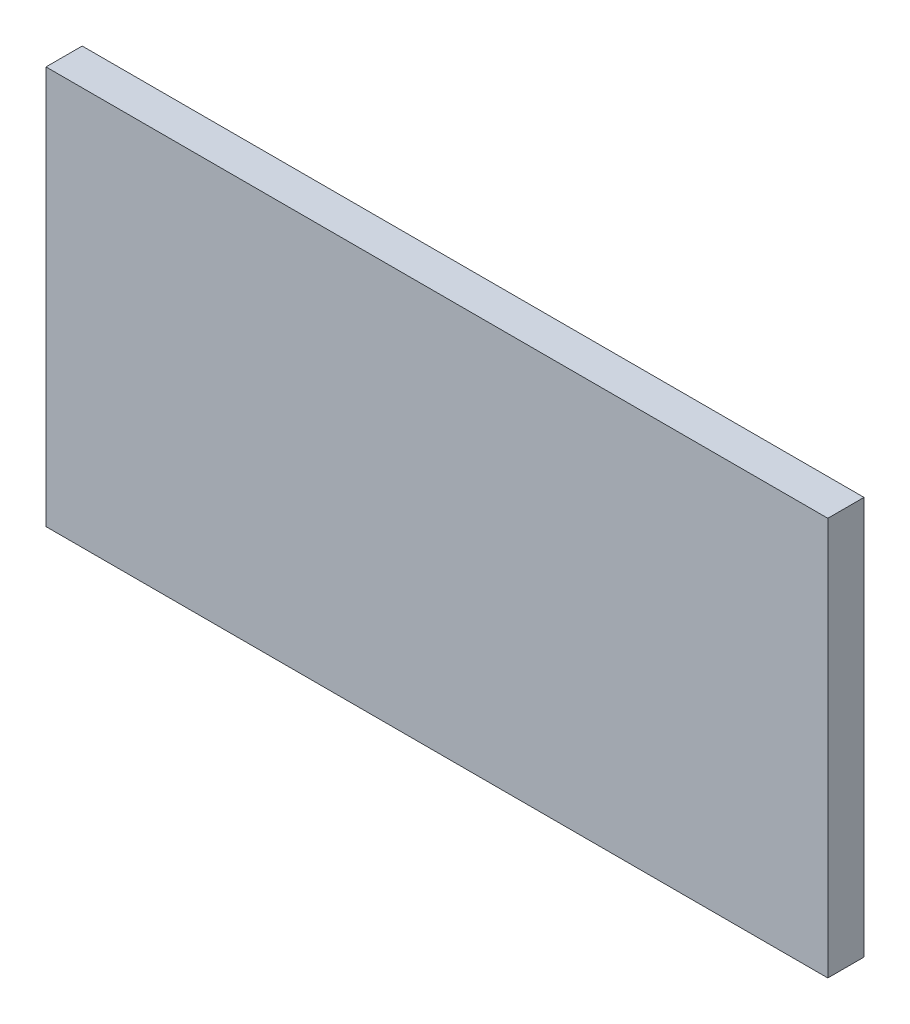
SolidWorks part; units mm, degrees
ref_plane "Front Plane" through (0, 0, 0) normal (0, 0, 1) x (1, 0, 0)
ref_plane "Top Plane" through (0, 0, 0) normal (0, 1, 0) x (1, 0, 0)
ref_plane "Right Plane" through (0, 0, 0) normal (1, 0, 0) x (0, 0, -1)
sketch "Sketch1" plane through (0, 0, 0) normal (0, 0, 1) x (1, 0, 0)
  line L1 (-54, 27.5) -> (54, 27.5)
  line L2 (-54, 27.5) -> (-54, -27.5)
  line L3 (-54, -27.5) -> (54, -27.5)
  line L4 (54, 27.5) -> (54, -27.5)
  line L5 (-54, 27.5) -> (54, -27.5) construction
  line L6 (-54, -27.5) -> (54, 27.5) construction
  point P0 (0, 0)
  dimension "D1" = 108
  dimension "D2" = 55
extrude "Boss-Extrude1" add sketch "Sketch1" along normal blind 5
